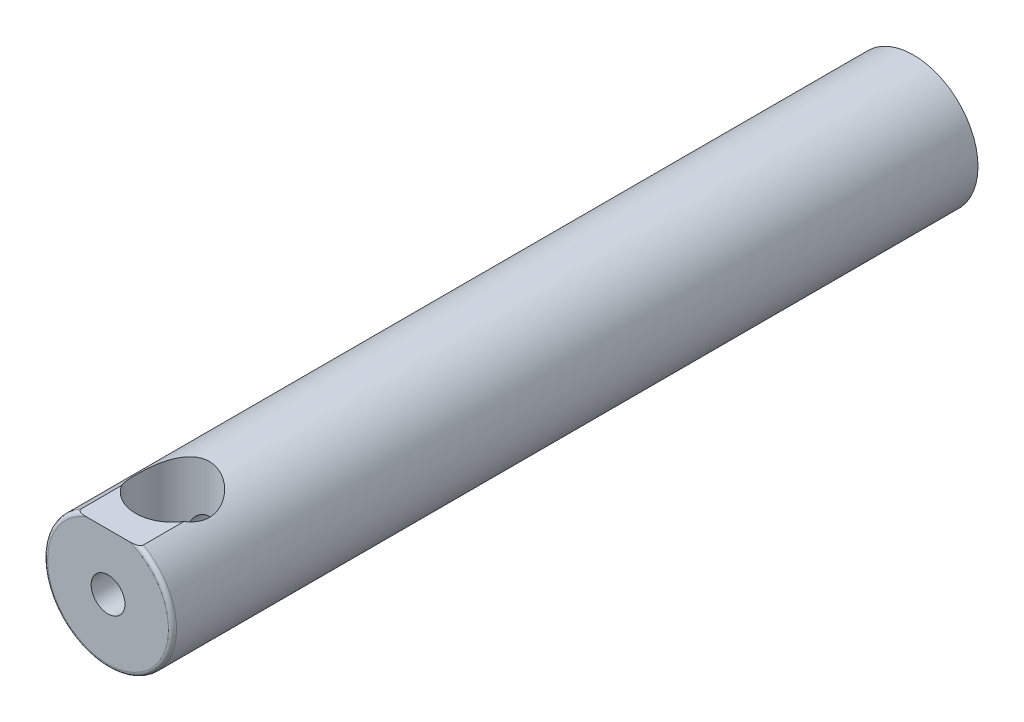
SolidWorks part; units mm, degrees
ref_plane "Ön Düzlem" through (0, 0, 0) normal (0, 0, 1) x (1, 0, 0)
ref_plane "Üst Düzlem" through (0, 0, 0) normal (0, 1, 0) x (1, 0, 0)
ref_plane "Sağ Düzlem" through (0, 0, 0) normal (1, 0, 0) x (0, 0, -1)
sketch "Çizim1" plane through (0, 0, 0) normal (0, 0, 1) x (1, 0, 0)
  circle A0 centre (0, 0) radius 8
extrude "Yükseklik-Ekstrüzyon1" add sketch "Çizim1" along normal blind 100
fillet "Radyus1" radius 0.5 1 edges at (8, 0, 100)
hole_wizard "M5x0.8 Tapped Hole1" positions "3B Çizim1" profile "Çizim3" tap size "M5x0.8" standard "Ansi Metric"
sketch3d "3B Çizim1"
  line L0 (0, 0, 99.5) -> (0, 0, 0) construction
  point P0 (0, 0, 0)
  point P4 (0, 0, 100)
sketch "Çizim3" plane through (0, 0, 100) normal (1, 0, 0) x (0, -1, 0)
  line L0 (0, 0) -> (0, 23.6618)
  line L1 (0, 23.6618) -> (2.1, 22.4)
  line L2 (2.1, 22.4) -> (2.1, 0)
  line L5 (2.1, 0) -> (0, 0)
  line L10 (0, 23.6618) -> (-2.1, 22.4) construction
  line L11 (0, -6.35) -> (0, 107.95) construction
  dimension "Tap Drill Dia." = 4.2
  dimension "Tap Drill Depth" = 22.4
  dimension "Drill Angle" = 118
cosmetic thread "Delik Dişi1" parameters "D1"=20, "D2"=5
cosmetic thread "Delik Dişi2" parameters "D1"=20, "D2"=5
sketch "Çizim4" plane through (0, 0, 100) normal (0, 0, 1) x (1, 0, 0)
  line L0 (3.873, 7) -> (-3.873, 7)
  line L1 (-3.873, 8) -> (3.873, 8)
  line L2 (3.873, 8) -> (3.873, 7)
  line L3 (-3.873, 8) -> (-3.873, 7)
extrude "Kes-Ekstrüzyon2" cut sketch "Çizim4" against normal blind 8
sketch "Croquis1" plane through (0, 0, 0) normal (0, 1, 0) x (1, 0, 0)
  line L0 (-3.873, -92) -> (3.873, -92) construction
  circle A0 centre (0, -92) radius 4.5792
extrude "Cortar-Extruir1" cut sketch "Croquis1" against normal through all both and the other way through all
